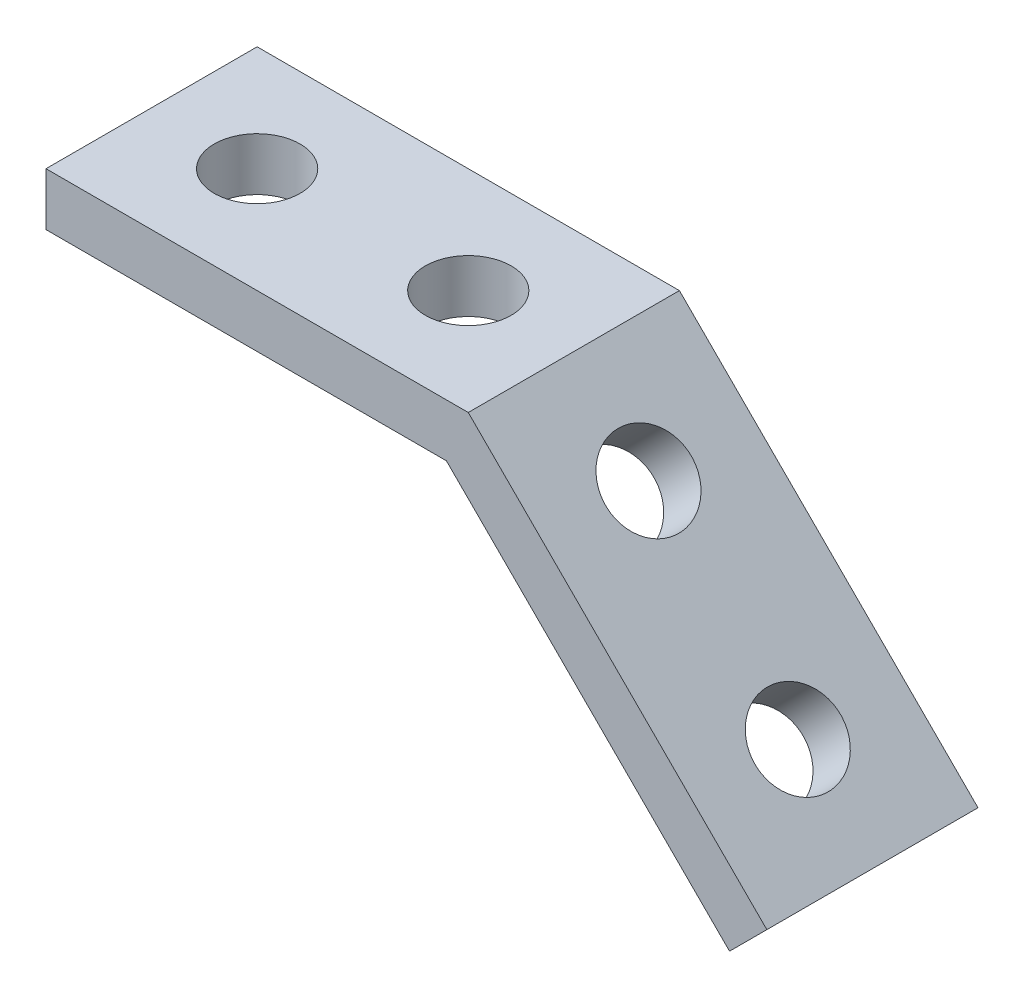
SolidWorks part; units mm, degrees
ref_plane "Front Plane" through (0, 0, 0) normal (0, 0, 1) x (1, 0, 0)
ref_plane "Top Plane" through (0, 0, 0) normal (0, 1, 0) x (1, 0, 0)
ref_plane "Right Plane" through (0, 0, 0) normal (1, 0, 0) x (0, 0, -1)
sketch "Sketch1" plane through (0, 0, 0) normal (0, 0, 1) x (1, 0, 0)
  line L0 (-102.3701, 43.9995) -> (-76.9701, 43.9995)
  line L1 (-76.9701, 43.9995) -> (-59.0096, 26.039)
  line L2 (-59.0096, 26.039) -> (-61.2546, 23.7939)
  line L3 (-61.2546, 23.7939) -> (-78.2852, 40.8245)
  line L4 (-78.2852, 40.8245) -> (-102.3701, 40.8245)
  line L5 (-102.3701, 40.8245) -> (-102.3701, 43.9995)
  dimension "D1" = 3.175
  dimension "D2" = 25.4
  dimension "D3" = 3.175
  dimension "D4" = 135
  dimension "D5" = 25.4
  dimension "D6" = 135
extrude "Boss-Extrude1" add sketch "Sketch1" along normal blind 12.7
sketch "Sketch2" plane through (0, 43.9995, 0) normal (0, 1, 0) x (1, 0, 0)
  line L0 (-102.3701, -12.7) -> (-102.3701, 0) construction
  circle A0 centre (-96.0201, -6.35) radius 2.5797
  circle A1 centre (-83.3201, -6.35) radius 2.5797
  dimension "D3" = 5.1594
  dimension "D4" = 5.1594
  dimension "D1" = 19.05
  dimension "D2" = 6.35
extrude "Cut-Extrude1" cut sketch "Sketch2" against normal blind 12.7
sketch "Sketch3" plane through (-16.4853, -16.4853, 0) normal (0.7071, 0.7071, 0) x (0, 0, -1)
  line L0 (-12.7, 60.1384) -> (0, 60.1384) construction
  circle A0 centre (-6.35, 66.4884) radius 2.5797
  circle A1 centre (-6.35, 79.1884) radius 2.5797
  dimension "D3" = 5.1594
  dimension "D4" = 5.1594
  dimension "D1" = 19.05
  dimension "D2" = 6.35
extrude "Cut-Extrude2" cut sketch "Sketch3" against normal blind 12.7
